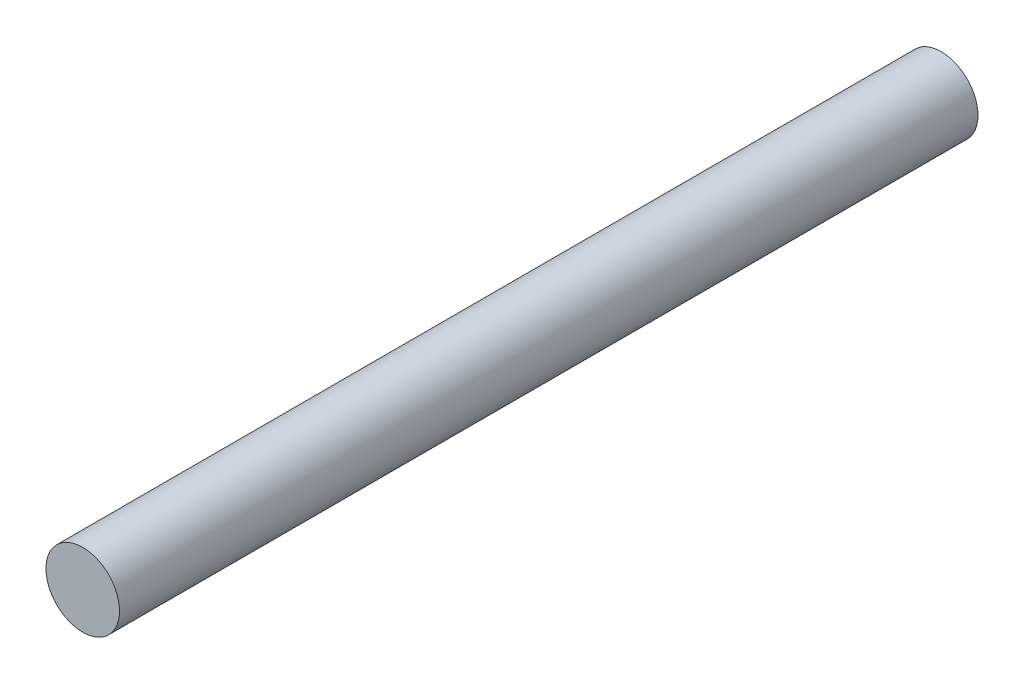
SolidWorks part; units mm, degrees
ref_plane "Płaszczyzna przednia" through (0, 0, 0) normal (0, 0, 1) x (1, 0, 0)
ref_plane "Płaszczyzna górna" through (0, 0, 0) normal (0, 1, 0) x (1, 0, 0)
ref_plane "Płaszczyzna prawa" through (0, 0, 0) normal (1, 0, 0) x (0, 0, -1)
sketch "Szkic2" plane through (0, 0, 0) normal (0, 0, 1) x (1, 0, 0)
  circle A0 centre (0, 0) radius 3
  dimension "D1" = 6
extrude "Dodanie-wyciągnięcie1" add sketch "Szkic2" along normal blind 70
